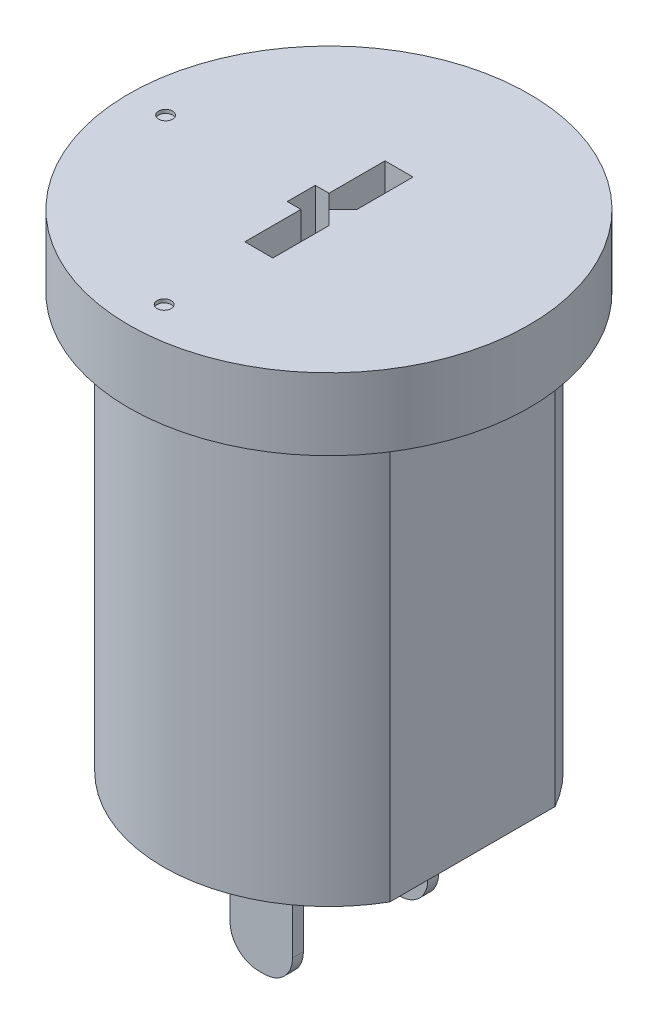
SolidWorks part; units mm, degrees
ref_plane "Front Plane" through (0, 0, 0) normal (0, 0, 1) x (1, 0, 0)
ref_plane "Top Plane" through (0, 0, 0) normal (0, 1, 0) x (1, 0, 0)
ref_plane "Right Plane" through (0, 0, 0) normal (1, 0, 0) x (0, 0, -1)
sketch "Sketch1" plane through (0, 0, 0) normal (0, 0, 1) x (1, 0, 0)
  line L0 (0, 19.2229) -> (0, -18.9885) construction
  line L1 (0, 17.6276) -> (-7.25, 17.6276)
  line L2 (-7.25, 17.6276) -> (-7.25, 15.0276)
  line L3 (-7.25, 15.0276) -> (-6, 15.0276)
  line L4 (-6, 15.0276) -> (-6, 0)
  line L5 (-6, 0) -> (0, 0)
  line L6 (0, 0) -> (0, 17.6276)
  dimension "D1" = 14.5
  dimension "D2" = 2.6
  dimension "D3" = 17.6276
  dimension "D4" = 12
revolve "Revolve1" add sketch "Sketch1" angle 360 about L0
sketch "Sketch2" plane through (0, 0, 0) normal (0, -1, 0) x (1, 0, 0)
  line L1 (-8.5029, 6.513) -> (-5.2, 6.513)
  line L2 (-8.5029, 6.513) -> (-8.5029, -7.3752)
  line L3 (-8.5029, -7.3752) -> (-5.2, -7.3752)
  line L4 (-5.2, 6.513) -> (-5.2, -7.3752)
  line L5 (5.2, 6.513) -> (8.5029, 6.513)
  line L6 (5.2, 6.513) -> (5.2, -7.3752)
  line L7 (5.2, -7.3752) -> (8.5029, -7.3752)
  line L8 (8.5029, 6.513) -> (8.5029, -7.3752)
  dimension "D1" = 10.4
  dimension "D2" = 5.2
extrude "Cut-Extrude1" cut sketch "Sketch2" against normal up to surface (15.0276 mm away) up to face at (0, 15.0276, 6)
sketch "Sketch3" plane through (0, 0, 0) normal (0, -1, 0) x (1, 0, 0)
  line L1 (-1.1303, 2.0563) -> (1.1303, 2.0563)
  line L2 (-1.1303, 2.0563) -> (-1.1303, 2.45)
  line L3 (-1.1303, 2.45) -> (1.1303, 2.45)
  line L4 (1.1303, 2.0563) -> (1.1303, 2.45)
  line L5 (-1.1303, 2.0563) -> (1.1303, 2.45) construction
  line L6 (-1.1303, 2.45) -> (1.1303, 2.0563) construction
  line L7 (-1.1303, -2.45) -> (1.1303, -2.45)
  line L8 (-1.1303, -2.45) -> (-1.1303, -2.8437)
  line L9 (-1.1303, -2.8437) -> (1.1303, -2.8437)
  line L10 (1.1303, -2.45) -> (1.1303, -2.8437)
  line L11 (-1.1303, -2.45) -> (1.1303, -2.8437) construction
  line L12 (-1.1303, -2.8437) -> (1.1303, -2.45) construction
  point P0 (0, 2.2532)
  point P5 (0, -2.6469)
  dimension "D1" = 4.9
  dimension "D2" = 2.45
  dimension "D3" = 0.3937
  dimension "D4" = 2.2606
extrude "Boss-Extrude1" add sketch "Sketch3" along normal blind 5.08
fillet "Fillet1" radius 1.016 4 edges at (1.1303, -5.08, -2.6469) (-1.1303, -5.08, -2.6469) (-1.1303, -5.08, 2.2532) (1.1303, -5.08, 2.2532)
sketch "Sketch4" plane through (0, 17.6276, 0) normal (0, 1, 0) x (1, 0, 0)
  line L0 (0.508, 2.54) -> (0.508, 0.5067)
  line L1 (0.508, 0.5067) -> (0, 0)
  line L2 (0, 0) -> (0.508, -0.5093)
  line L3 (0.508, -0.5093) -> (0.508, -2.54)
  line L4 (0.508, -2.54) -> (-0.508, -2.54)
  line L5 (-0.508, -2.54) -> (-0.508, -0.508)
  line L6 (-0.508, -0.508) -> (-1.0031, -0.508)
  line L7 (-1.0031, -0.508) -> (-1.0031, 0.508)
  line L8 (-1.0031, 0.508) -> (-0.508, 0.508)
  line L9 (-0.508, 0.508) -> (-0.508, 2.54)
  line L10 (-0.508, 2.54) -> (0.508, 2.54)
  point P8 (-1.0031, 0)
  point P13 (0, 2.54)
  dimension "D1" = 5.08
  dimension "D2" = 2.54
  dimension "D3" = 1.016
  dimension "D4" = 1.016
extrude "Cut-Extrude2" cut sketch "Sketch4" against normal blind 2.54
sketch "Sketch5" plane through (0, 17.6276, 0) normal (0, 1, 0) x (1, 0, 0)
  circle A0 centre (-5.916, 0) radius 0.254
  circle A1 centre (0, -5.9691) radius 0.254
  dimension "D1" = 0.508
extrude "Cut-Extrude3" cut sketch "Sketch5" against normal blind 0.127
